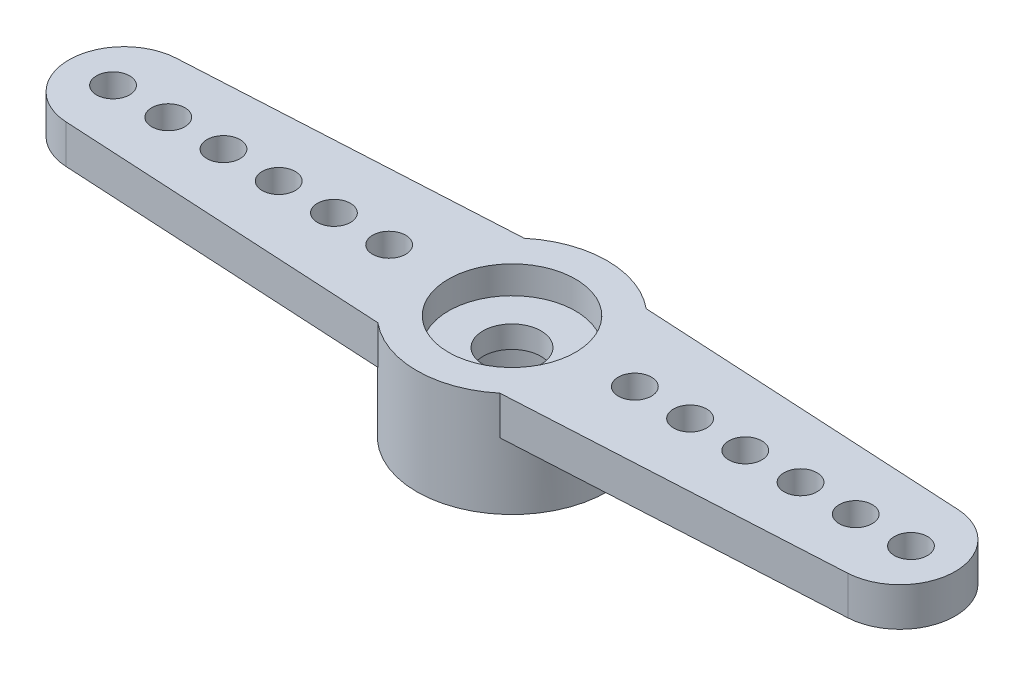
SolidWorks part; units mm, degrees
material "PVC Rígido"
ref_plane "Plano frontal" through (0, 0, 0) normal (0, 0, 1) x (1, 0, 0)
ref_plane "Plano superior" through (0, 0, 0) normal (0, 1, 0) x (1, 0, 0)
ref_plane "Plano direito" through (0, 0, 0) normal (1, 0, 0) x (0, 0, -1)
sketch "Esboço1" plane through (0, 0, 0) normal (0, 1, 0) x (1, 0, 0)
  line L0 (0, 0) -> (-14.05, 0) construction
  line L1 (-14.1591, 1.997) -> (-2.2091, 2.65)
  line L2 (-2.2091, -2.65) -> (-14.1591, -1.997)
  arc A0 (-2.2091, -2.65) -> (-2.2091, 2.65) centre (0, 0) ccw
  arc A1 (-14.1591, 1.997) -> (-14.1591, -1.997) centre (-14.05, 0) ccw
  dimension "D1" = 6.9
  dimension "D2" = 4
  dimension "D3" = 19.5
  dimension "D4" = 5.3
extrude "Ressalto-extrusão1" add sketch "Esboço1" against normal blind 1.4
sketch "Esboço2" plane through (0, -1.4, 0) normal (0, -1, 0) x (1, 0, 0)
  arc A0 (-2.2091, -2.65) -> (-2.2091, 2.65) centre (0, 0) ccw construction
  circle A1 centre (0, 0) radius 3.45
extrude "Ressalto-extrusão2" add sketch "Esboço2" along normal offset from surface (2.4 mm away) 3.8 up to face at (-7.242, 0, 0)
hole_wizard "Furo4" positions "Esboço9" profile "Esboço10" legacy end condition through all
sketch "Esboço9" plane through (0, 0, 0) normal (0, 1, 0) x (1, 0, 0)
  line L1 (-14.45, 0) -> (0, 0) construction
  arc A2 (-14.1591, 1.997) -> (-14.1591, -1.997) centre (-14.05, 0) ccw construction
  point P0 (-14.45, 0)
  point P19 (-16.05, 0)
  dimension "D1" = 1.6
sketch "Esboço10" plane through (-14.45, 0, 0) normal (1, 0, 0) x (0, 0, 1)
  line L0 (0, 0) -> (0, 3.8)
  line L1 (0, 3.8) -> (0.6, 3.8)
  line L2 (0.6, 3.8) -> (0.6, 0)
  line L3 (0.6, 0) -> (0, 0)
  line L4 (0, 110) -> (0, -10) construction
  dimension "Diameter" = 1.2
  dimension "Depth" = 3.8
pattern_linear "Padrão linear1" count 6 spacing 2 along (1, 0, 0) of "Furo4"
pattern_circular "PadrãoCircular2" count 2 over 360 about axis through (0, 0, 0) along (0, 1, 0) of "Ressalto-extrusão1", "Furo4", "Padrão linear1"
hole_wizard "Furo1" positions "Esboço3" profile "Esboço4" legacy
sketch "Esboço3" plane through (0, -3.8, 0) normal (0, -1, 0) x (-1, 0, 0)
  point P0 (0, 0)
sketch "Esboço4" plane through (0, -3.8, 0) normal (1, 0, 0) x (0, 0, -1)
  line L0 (0, 0) -> (0, 2)
  line L1 (0, 2) -> (2.475, 2)
  line L2 (2.475, 2) -> (2.475, 0)
  line L3 (2.475, 0) -> (0, 0)
  line L4 (0, 110) -> (0, -10) construction
  dimension "Diameter" = 4.95
  dimension "Depth" = 2
hole_wizard "Furo2" positions "Esboço5" profile "Esboço6" legacy
sketch "Esboço5" plane through (0, 0, 0) normal (0, 1, 0) x (1, 0, 0)
  point P0 (0, 0)
sketch "Esboço6" plane through (0, 0, 0) normal (1, 0, 0) x (0, 0, 1)
  line L0 (0, 0) -> (0, 1)
  line L1 (0, 1) -> (2.3, 1)
  line L2 (2.3, 1) -> (2.3, 0)
  line L3 (2.3, 0) -> (0, 0)
  line L4 (0, 110) -> (0, -10) construction
  dimension "Diameter" = 4.6
  dimension "Depth" = 1
hole_wizard "Furo3" positions "Esboço7" profile "Esboço8" legacy end condition through all
sketch "Esboço7" plane through (0, 0, 0) normal (0, 1, 0) x (1, 0, 0)
  point P0 (0, 0)
sketch "Esboço8" plane through (0, 0, 0) normal (1, 0, 0) x (0, 0, 1)
  line L0 (0, 0) -> (0, 3.8)
  line L1 (0, 3.8) -> (1.05, 3.8)
  line L2 (1.05, 3.8) -> (1.05, 0)
  line L3 (1.05, 0) -> (0, 0)
  line L4 (0, 110) -> (0, -10) construction
  dimension "Diameter" = 2.1
  dimension "Depth" = 3.8
sketch "Esboço11" plane through (0, -3.8, 0) normal (0, -1, 0) x (1, 0, 0)
  line L0 (-0.0981, 2.4731) -> (0, 2.375)
  line L1 (0, 2.375) -> (0.0981, 2.4731)
  line L2 (0, 0) -> (0, 2.475) construction
  circle A0 centre (0, 0) radius 2.375 construction
  circle A1 centre (0, 0) radius 2.475
  arc A2 (0.0981, 2.4731) -> (-0.0981, 2.4731) centre (0, 0) ccw
  dimension "D3" = 4.75
  dimension "D2" = 0.1
  dimension "D1" = 0
extrude "Ressalto-extrusão3" [suppressed] add sketch "Esboço11" against normal up to surface (2 mm away)
pattern_circular "PadrãoCircular1" [suppressed] count 60 over 360
